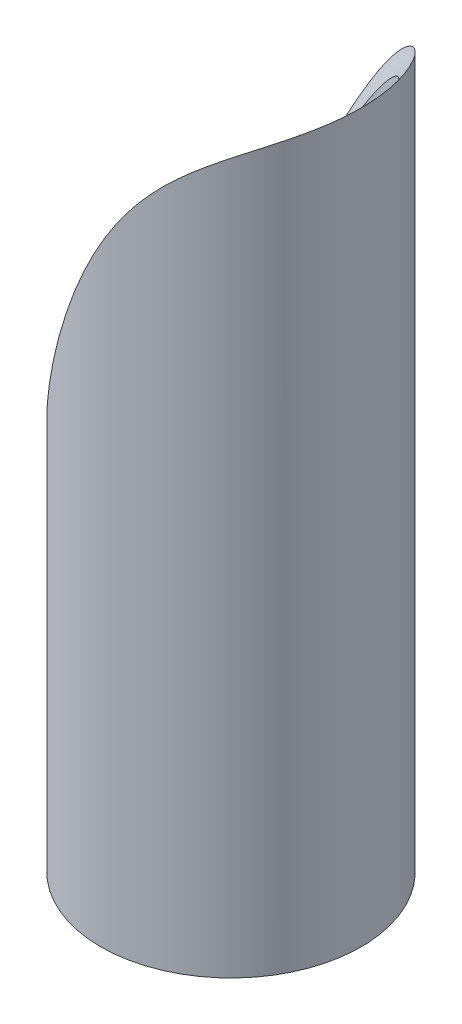
SolidWorks part; units mm, degrees
ref_plane "Front Plane" through (0, 0, 0) normal (0, 0, 1) x (1, 0, 0)
ref_plane "Top Plane" through (0, 0, 0) normal (0, 1, 0) x (1, 0, 0)
ref_plane "Right Plane" through (0, 0, 0) normal (1, 0, 0) x (0, 0, -1)
sketch "Sketch1" plane through (0, 0, 0) normal (0, 1, 0) x (1, 0, 0)
  circle A0 centre (0, 0) radius 10.25
  circle A1 centre (0, 0) radius 11.25
  dimension "D1" = 1
  dimension "D2" = 20.5
extrude "Boss-Extrude1" add sketch "Sketch1" along normal blind 75
sketch "Sketch2" plane through (0, 0, 0) normal (0, 0, 1) x (1, 0, 0)
  line L0 (0, 0) -> (0, 75) construction
  line L1 (-11.25, 0) -> (11.25, 0) construction
  line L2 (0, 9.6513) -> (-37.7291, 9.6513) construction
  line L3 (-37.7291, 9.6513) -> (15.5739, 101.9747)
  dimension "D1" = 75
  dimension "D2" = 60
ref_plane "Plane1" through (15.5739, 101.9747, 0) normal (0.5, 0.866, 0) x (0.866, -0.5, 0)
sketch "Sketch3" plane through (15.5739, 101.9747, 0) normal (0.5, 0.866, 0) x (0.866, -0.5, 0)
  line L0 (32.6743, 0) -> (0, 0) construction
  circle A0 centre (0, 0) radius 15.875
  dimension "D1" = 31.75
sweep "Cut-Sweep1" cut profiles "Sketch3" path "Sketch2"
